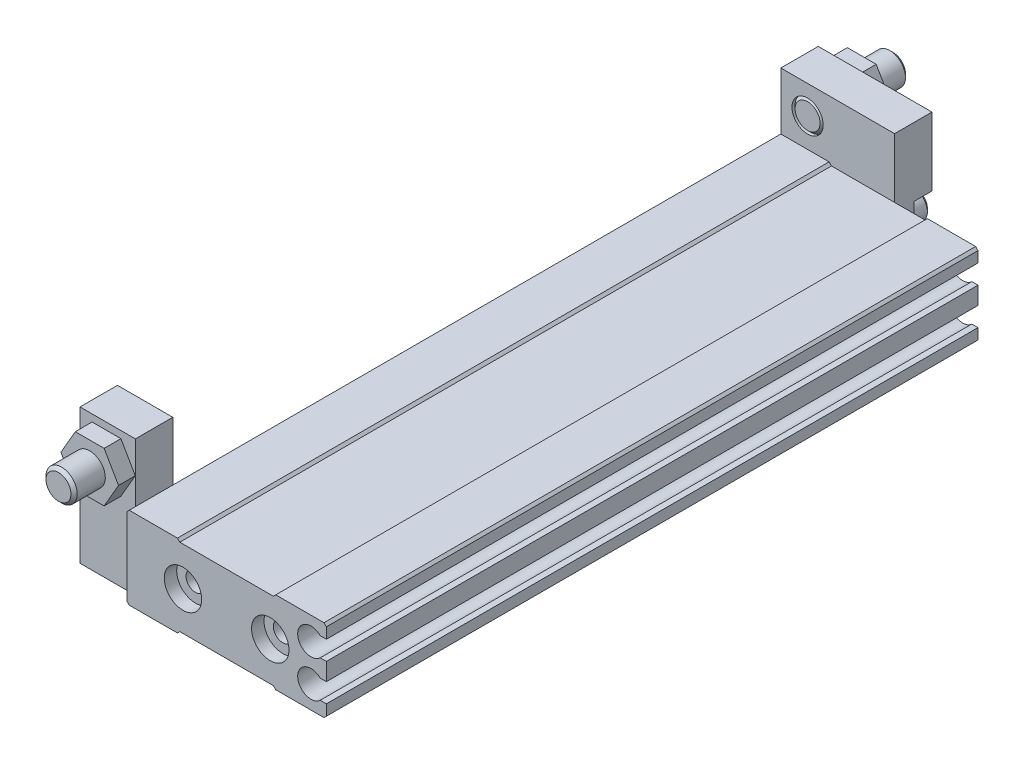
SolidWorks part; units mm, degrees
ref_plane "Front" through (0, 0, 0) normal (0, 0, 1) x (1, 0, 0)
ref_plane "Top" through (0, 0, 0) normal (0, 1, 0) x (1, 0, 0)
ref_plane "Right" through (0, 0, 0) normal (1, 0, 0) x (0, 0, -1)
ref_plane "Plane4" through (0, 0, 0) normal (0, 0, 1) x (-1, 0, 0)
sketch "Sketch1" plane through (0, 0, 57.15) normal (0, 0, 1) x (-1, 0, 0)
  line L0 (15.619, 6.5913) -> (16, 6.2103)
  line L1 (-7.5, 6.2103) -> (7.5, 6.2103)
  line L2 (15.619, 6.5913) -> (7.881, 6.5913)
  line L3 (-7.881, 6.5913) -> (-15.619, 6.5913)
  line L4 (7.5, 6.2103) -> (7.881, 6.5913)
  line L5 (-7.5, 6.2103) -> (-7.881, 6.5913)
  line L6 (-16, 6.2103) -> (-16, 4.4831)
  line L7 (-16, -6.2103) -> (-15.619, -6.5913)
  line L8 (-7.5, -6.2103) -> (-7.881, -6.5913)
  line L9 (-16, 1.4097) -> (-16, -1.4097)
  line L10 (-16, -4.4831) -> (-16, -6.2103)
  line L11 (-16, 6.2103) -> (-15.619, 6.5913)
  line L12 (16, 6.2103) -> (16, -6.2103)
  line L14 (-50, 0) -> (50, 0) construction
  line L15 (-7.881, -6.5913) -> (-15.619, -6.5913)
  line L16 (-15.0137, -4.4831) -> (-16, -4.4831)
  line L17 (-11.4, 6.5913) -> (-11.4, 2.9464) construction
  line L18 (-7.5, -6.2103) -> (7.5, -6.2103)
  line L19 (7.5, -6.2103) -> (7.881, -6.5913)
  line L20 (16, -6.2103) -> (15.619, -6.5913)
  line L22 (-16, 0) -> (16, 0) construction
  line L23 (0, 0) -> (0, 6.2103) construction
  line L26 (15.619, -6.5913) -> (7.881, -6.5913)
  line L27 (-15.0137, -1.4097) -> (-16, -1.4097)
  line L28 (-15.0137, 1.4097) -> (-16, 1.4097)
  line L29 (-15.0137, 4.4831) -> (-16, 4.4831)
  arc A0 (-15.0137, 1.4097) -> (-15.0137, 4.4831) centre (-13.5336, 2.9464) ccw
  arc A1 (-15.0137, -4.4831) -> (-15.0137, -1.4097) centre (-13.5336, -2.9464) ccw
  dimension "D5" = 4.2672
  dimension "D1" = 13.1826
  dimension "D2" = 45
  dimension "D3" = 0.381
  dimension "D4" = 4.6
  dimension "D6" = 15
  dimension "D7" = 5.8928
  dimension "D8" = 3.0734
extrude "Base-Extrude" add sketch "Sketch1" along normal up to surface (104.5 mm away)
ref_plane "Plane8" through (0, 0, 55.15) normal (0, 0, 1) x (1, 0, 0)
sketch "Sketch2" plane through (0, 0, 57.15) normal (0, 0, -1) x (-1, 0, 0)
  line L0 (22.7583, 0) -> (-22.7583, 0) construction
  line L5 (0, 6.2103) -> (0, -6.2103) construction
  line L6 (7.5, 6.2103) -> (-7.5, 6.2103) construction
  line L7 (-7.5, -6.2103) -> (7.5, -6.2103) construction
  circle A0 centre (-7, 0) radius 3
  circle A1 centre (7, 0) radius 3
  dimension "D1" = 6
  dimension "D2" = 14
extrude "Cut-Extrude1" cut sketch "Sketch2" along normal up to surface (103.2 mm away)
sketch "Sketch4" plane through (0, 0, 55.15) normal (0, 0, 1) x (1, 0, 0)
  circle A2 centre (7, 0) radius 3 construction
  circle A3 centre (-7, 0) radius 3 construction
  circle A4 centre (7, 0) radius 3
  circle A5 centre (-7, 0) radius 3
extrude "Boss-Extrude1" add sketch "Sketch4" against normal blind 10
sketch "Sketch19" plane through (0, 0, 55.15) normal (0, 0, 1) x (1, 0, 0)
  circle A0 centre (7, 0) radius 1.5
  circle A1 centre (-7, 0) radius 1.5
  circle A2 centre (-7, 0) radius 3 construction
  circle A3 centre (7, 0) radius 3 construction
  dimension "D1" = 3
extrude "Cut-Extrude3" cut sketch "Sketch19" against normal up to next
hole_wizard "#4-40 Tapped Hole2" positions "Sketch21" profile "Sketch20" tap size "#4-40" standard "Ansi Inch"
sketch "Sketch21" plane through (0, -6.2103, 0) normal (0, -1, 0) x (1, 0, 0)
  point P0 (0, 41.85)
  point P1 (0, 26.85)
sketch "Sketch20" plane through (0, -6.2103, 41.85) normal (1, 0, 0) x (0, 0, -1)
  line L0 (0, 0) -> (0, 9.5438)
  line L1 (0, 9.5438) -> (1.1303, 8.8646)
  line L2 (1.1303, 8.8646) -> (1.1303, 5.6896)
  line L3 (1.1303, 5.6896) -> (1.4224, 5.6896)
  line L4 (1.4224, 5.6896) -> (1.4224, 0)
  line L5 (1.4224, 0) -> (0, 0)
  line L10 (0, 9.5438) -> (-1.1303, 8.8646) construction
  line L11 (0, -6.35) -> (0, 107.95) construction
  dimension "Tap Drill Dia." = 2.2606
  dimension "Tap Drill Depth" = 8.8646
  dimension "Thread Dia." = 2.8448
  dimension "Thread Depth" = 5.6896
  dimension "Drill Angle" = 118
hole_wizard "#3-48 Tapped Hole1" positions "Sketch23" profile "Sketch22" tap size "#3-56" standard "Ansi Inch"
sketch "Sketch23" plane through (0, 0, -47.35) normal (0, 0, -1) x (-1, 0, 0)
  line L0 (7.881, -6.5913) -> (15.619, -6.5913) construction
  point P0 (13, -4.0913)
  point P1 (13, 3.9087)
  point P2 (0, -4.0913)
  point P3 (0, 1.9087)
  dimension "D1" = 2.5
  dimension "D2" = 8
  dimension "D3" = 13
  dimension "D4" = 13
  dimension "D5" = 6
sketch "Sketch22" plane through (-13, -4.0913, -47.35) normal (1, 0, 0) x (0, 1, 0)
  line L0 (0, 0) -> (0, 7.9282)
  line L1 (0, 7.9282) -> (1.0414, 7.3025)
  line L2 (1.0414, 7.3025) -> (1.0414, 5.0292)
  line L3 (1.0414, 5.0292) -> (1.2573, 5.0292)
  line L4 (1.2573, 5.0292) -> (1.2573, 0)
  line L5 (1.2573, 0) -> (0, 0)
  line L10 (0, 7.9282) -> (-1.0414, 7.3025) construction
  line L11 (0, -6.35) -> (0, 107.95) construction
  dimension "Tap Drill Dia." = 2.0828
  dimension "Tap Drill Depth" = 7.3025
  dimension "Thread Dia." = 2.5146
  dimension "Thread Depth" = 5.0292
  dimension "Drill Angle" = 118
hole_wizard "Hole1" positions "Sketch25" profile "Sketch24" legacy
sketch "Sketch25" plane through (0, -6.5913, 0) normal (0, -1, 0) x (1, 0, 0)
  point P0 (-12, 44.15)
sketch "Sketch24" plane through (-12, -6.5913, 44.15) normal (1, 0, 0) x (0, 0, -1)
  line L0 (0, 0) -> (0, 2.54)
  line L1 (0, 2.54) -> (1.5939, 2.54)
  line L2 (1.5939, 2.54) -> (1.5939, 0)
  line L3 (1.5939, 0) -> (0, 0)
  line L4 (0, 110) -> (0, -10) construction
  dimension "Diameter" = 3.1877
  dimension "Depth" = 2.54
sketch "Sketch27" plane through (0, -6.5913, 0) normal (0, -1, 0) x (1, 0, 0)
  line L0 (-16, 16.15) -> (-12, 16.15) construction
  line L1 (-16, 57.15) -> (-16, -47.35) construction
  line L2 (-16, 18.15) -> (-12, 18.15) construction
  line L3 (-16, 14.15) -> (-12, 14.15) construction
  line L4 (-13.5939, 16.5561) -> (-13.5939, 15.7438)
  line L5 (-10.4062, 16.5561) -> (-10.4062, 15.7438)
  arc A0 (-13.5939, 15.7438) -> (-10.4062, 15.7438) centre (-12, 15.7438) ccw
  arc A1 (-10.4062, 16.5561) -> (-13.5939, 16.5561) centre (-12, 16.5561) ccw
  dimension "D1" = 3.1877
  dimension "D2" = 4
extrude "Cut-Extrude4" cut sketch "Sketch27" against normal blind 2.5
hole_wizard "#10-32 Tapped Hole1" positions "Sketch29" profile "Sketch28" tap size "#10-32" standard "Ansi Inch"
sketch "Sketch29" plane through (-16, 0, 0) normal (-1, 0, 0) x (0, 0, 1)
  line L0 (57.15, 6.2103) -> (57.15, -6.2103) construction
  line L1 (-47.35, -6.2103) -> (-47.35, 6.2103) construction
  line L2 (-47.35, -6.5913) -> (57.15, -6.5913) construction
  point P0 (45.85, -0.0913)
  point P1 (-40.65, -0.0913)
  dimension "D1" = 11.3
  dimension "D2" = 6.7
  dimension "D3" = 6.5
sketch "Sketch28" plane through (-16, -0.0913, 45.85) normal (0, 1, 0) x (0, 0, 1)
  line L0 (0, 0) -> (0, 14.8277)
  line L1 (0, 14.8277) -> (2.0193, 13.6144)
  line L2 (2.0193, 13.6144) -> (2.0193, 9.652)
  line L3 (2.0193, 9.652) -> (2.413, 9.652)
  line L4 (2.413, 9.652) -> (2.413, 0)
  line L5 (2.413, 0) -> (0, 0)
  line L10 (0, 14.8277) -> (-2.0193, 13.6144) construction
  line L11 (0, -6.35) -> (0, 107.95) construction
  dimension "Tap Drill Dia." = 4.0386
  dimension "Tap Drill Depth" = 13.6144
  dimension "Thread Dia." = 4.826
  dimension "Thread Depth" = 9.652
  dimension "Drill Angle" = 118
sketch "Sketch30" plane through (0, 0, -47.35) normal (0, 0, -1) x (-1, 0, 0)
  line L0 (-7.5, -6.2103) -> (7.5, -6.2103) construction
  line L1 (-2.618, 15.7607) -> (15.619, 15.7607)
  line L2 (-2.618, 15.7607) -> (-2.618, -5.8293)
  line L3 (-2.618, -5.8293) -> (15.619, -5.8293)
  line L4 (15.619, 15.7607) -> (15.619, -5.8293)
  line L5 (16, -6.2103) -> (16, 6.2103) construction
  dimension "D1" = 0.381
  dimension "D2" = 0.381
  dimension "D3" = 21.59
  dimension "D4" = 18.237
extrude "Boss-Extrude2" add sketch "Sketch30" along normal blind 6
sketch "Sketch31" plane through (0, 0, -53.35) normal (0, 0, -1) x (-1, 0, 0)
  line L0 (15.9478, 11.2316) -> (13.6384, 15.2316)
  line L1 (13.6384, 15.2316) -> (9.0196, 15.2316)
  line L2 (9.0196, 15.2316) -> (6.7102, 11.2316)
  line L3 (6.7102, 11.2316) -> (9.0196, 7.2316)
  line L4 (9.0196, 7.2316) -> (13.6384, 7.2316)
  line L5 (13.6384, 7.2316) -> (15.9478, 11.2316)
  line L6 (15.619, 15.7607) -> (-2.618, 15.7607) construction
  line L7 (15.619, -5.8293) -> (15.619, 15.7607) construction
  circle A0 centre (11.329, 11.2316) radius 4.6188 construction
  dimension "D1" = 4.5291
  dimension "D2" = 4.29
  dimension "D3" = 8
sketch "Sketch48" plane through (0, 0, -53.35) normal (0, 0, -1) x (-1, 0, 0)
  line L0 (15.619, -5.8293) -> (15.619, 6.7947)
  line L1 (15.619, -5.8293) -> (15.619, 15.7607) construction
  line L2 (15.619, 6.7947) -> (12.999, 6.7947)
  line L3 (10.489, 4.2847) -> (10.489, -5.8293)
  line L4 (10.489, -5.8293) -> (15.619, -5.8293)
  line L5 (-2.618, -5.8293) -> (2.512, -5.8293)
  line L6 (2.512, -5.8293) -> (2.512, 2.2807)
  line L7 (0.002, 4.7907) -> (-2.618, 4.7907)
  line L8 (-2.618, 15.7607) -> (-2.618, -5.8293) construction
  line L9 (-2.618, 4.7907) -> (-2.618, -5.8293)
  arc A0 (10.489, 4.2847) -> (12.999, 6.7947) centre (12.999, 4.2847) cw
  arc A1 (0.002, 4.7907) -> (2.512, 2.2807) centre (0.002, 2.2807) cw
  point P9 (10.489, 6.7947)
  dimension "D3" = 2.51
  dimension "D4" = 2.51
  dimension "D1" = 12.624
  dimension "D2" = 5.13
  dimension "D5" = 10.62
extrude "Cut-Extrude9" cut sketch "Sketch48" against normal blind 2.87
extrude "Boss-Extrude3" add sketch "Sketch31" along normal blind 2.6924
sketch "Sketch35" plane through (0, 0, -50.48) normal (0, 0, -1) x (-1, 0, 0)
  circle A0 centre (13, 3.9087) radius 2.25
  circle A1 centre (0, 1.9087) radius 2.25
  circle A2 centre (0, -4.0913) radius 2.25
  circle A3 centre (13, -4.0913) radius 2.25
  circle A4 centre (13, -4.0913) radius 1.2573 construction
  circle A7 centre (0, 1.9087) radius 1.2573 construction
  circle A8 centre (0, -4.0913) radius 1.2573 construction
  circle A9 centre (13, 3.9087) radius 1.2573 construction
  dimension "D1" = 4.5
extrude "Boss-Extrude5" add sketch "Sketch35" along normal blind 3
chamfer "Chamfer2" distance 0.5 angle 45 4 edges at (-15.25, 3.9087, -53.48) (-15.25, -4.0913, -53.48) (-2.25, -4.0913, -53.48) (-2.25, 1.9087, -53.48)
ref_plane "Plane9" through (0, 0, 49.65) normal (0, 0, 1) x (1, 0, 0)
sketch "Sketch36" plane through (0, 0, 49.65) normal (0, 0, 1) x (1, 0, 0)
  line L0 (-16.127, 15.4987) -> (-16.127, 4.5913)
  line L1 (-25, 15.4987) -> (-16.127, 15.4987)
  line L2 (-25, 15.4987) -> (-25, -6.2213)
  line L3 (-25, -6.2213) -> (-16, -6.2213)
  line L4 (-16, 4.5913) -> (-16, -6.2213)
  line L5 (-16.127, 4.5913) -> (-16, 4.5913)
  line L7 (-16, 15.9087) -> (-16, -5.1213) construction
  line L8 (-15.619, -6.5913) -> (-7.881, -6.5913) construction
  line L11 (16, 6.5913) -> (-16, 6.5913) construction
  dimension "D1" = 9
  dimension "D2" = 0.127
  dimension "D3" = 21.72
  dimension "D4" = 0.37
  dimension "D5" = 2
extrude "Boss-Extrude6" add sketch "Sketch36" along normal blind 6
sketch "Sketch37" plane through (0, 0, 55.65) normal (0, 0, 1) x (1, 0, 0)
  line L0 (-25, 15.4987) -> (-25, -6.2213) construction
  line L1 (-18.4506, 14.3687) -> (-23.0694, 14.3687)
  line L2 (-23.0694, 14.3687) -> (-25.3788, 10.3687)
  line L3 (-25.3788, 10.3687) -> (-23.0694, 6.3687)
  line L4 (-23.0694, 6.3687) -> (-18.4506, 6.3687)
  line L5 (-18.4506, 6.3687) -> (-16.1412, 10.3687)
  line L8 (-16.1412, 10.3687) -> (-18.4506, 14.3687)
  line L9 (-16.127, 15.4987) -> (-25, 15.4987) construction
  circle A0 centre (-20.76, 10.3687) radius 4 construction
  dimension "D1" = 4.24
  dimension "D2" = 5.13
  dimension "D3" = 8
extrude "Boss-Extrude7" add sketch "Sketch37" along normal blind 2.69
sketch "Sketch38" plane through (0, 0, 58.34) normal (0, 0, 1) x (1, 0, 0)
  line L0 (-16.1412, 10.3687) -> (-18.4506, 14.3687) construction
  line L1 (-25.3788, 10.3687) -> (-23.0694, 6.3687) construction
  line L2 (-18.4506, 14.3687) -> (-23.0694, 14.3687) construction
  circle A0 centre (-20.76, 10.3687) radius 4 construction
  circle A1 centre (-20.76, 10.3687) radius 2.5
  dimension "D1" = 5
ref_plane "Plane11" through (0, 10.3687, 0) normal (0, 1, 0) x (-1, 0, 0)
extrude "Cut-Extrude7" cut sketch "Sketch38" against normal up to next
sketch "Sketch44" plane through (0, 10.3687, 0) normal (0, 1, 0) x (-1, 0, 0)
  line L0 (20.76, 58.34) -> (20.76, 49.65) construction
  line L1 (18.4506, 58.34) -> (23.0694, 58.34) construction
  line L2 (9.7125, 49.65) -> (-9.7125, 49.65) construction
  line L4 (20.76, 63.35) -> (23.26, 63.35)
  line L5 (20.76, 63.35) -> (20.76, 49.65)
  line L6 (20.76, 49.65) -> (22.76, 49.65)
  line L7 (23.26, 63.35) -> (23.26, 50.15)
  line L8 (23.26, 50.15) -> (22.76, 49.65)
  line L10 (23.26, 49.65) -> (23.26, 58.34) construction
  line L11 (16.127, 49.65) -> (25, 49.65) construction
  line L12 (16.127, 55.65) -> (25, 55.65) construction
  dimension "D1" = 7.7
  dimension "D2" = 45
  dimension "D3" = 0.5
revolve "Boss-Revolve1" add sketch "Sketch44" angle 360 about L0
sketch "Sketch46" plane through (0, 0, -56.0424) normal (0, 0, -1) x (-1, 0, 0)
  line L0 (15.9478, 11.2316) -> (13.6384, 15.2316) construction
  line L1 (9.0196, 7.2316) -> (13.6384, 7.2316) construction
  line L2 (9.0196, 15.2316) -> (6.7102, 11.2316) construction
  circle A0 centre (11.329, 11.2316) radius 4 construction
  circle A1 centre (11.329, 11.2316) radius 2.5
  dimension "D1" = 5
extrude "Cut-Extrude8" cut sketch "Sketch46" against normal up to next
ref_plane "Plane12" through (0, 11.2316, 0) normal (0, 1, 0) x (-1, 0, 0)
sketch "Sketch47" plane through (0, 11.2316, 0) normal (0, 1, 0) x (-1, 0, 0)
  line L0 (15.619, -47.35) -> (-2.618, -47.35) construction
  line L2 (13.829, -56.0424) -> (13.829, -47.35) construction
  line L3 (13.329, -47.35) -> (11.329, -47.35)
  line L4 (11.329, -47.35) -> (11.329, -61.05)
  line L5 (13.829, -61.05) -> (13.829, -47.85)
  line L6 (11.329, -47.35) -> (11.329, -61.05) construction
  line L7 (11.329, -61.05) -> (13.829, -61.05)
  line L8 (13.829, -47.85) -> (13.329, -47.35)
  line L9 (15.619, -53.35) -> (-2.618, -53.35) construction
  line L10 (11.329, -47.35) -> (11.329, -56.0424) construction
  dimension "D1" = 45
  dimension "D2" = 0.5
  dimension "D3" = 7.7
revolve "Boss-Revolve2" add sketch "Sketch47" angle 360 about L6
chamfer "Chamfer3" distance 0.5 angle 45 2 edges at (-8.829, 11.2316, -61.05) (-18.26, 10.3687, 63.35)
